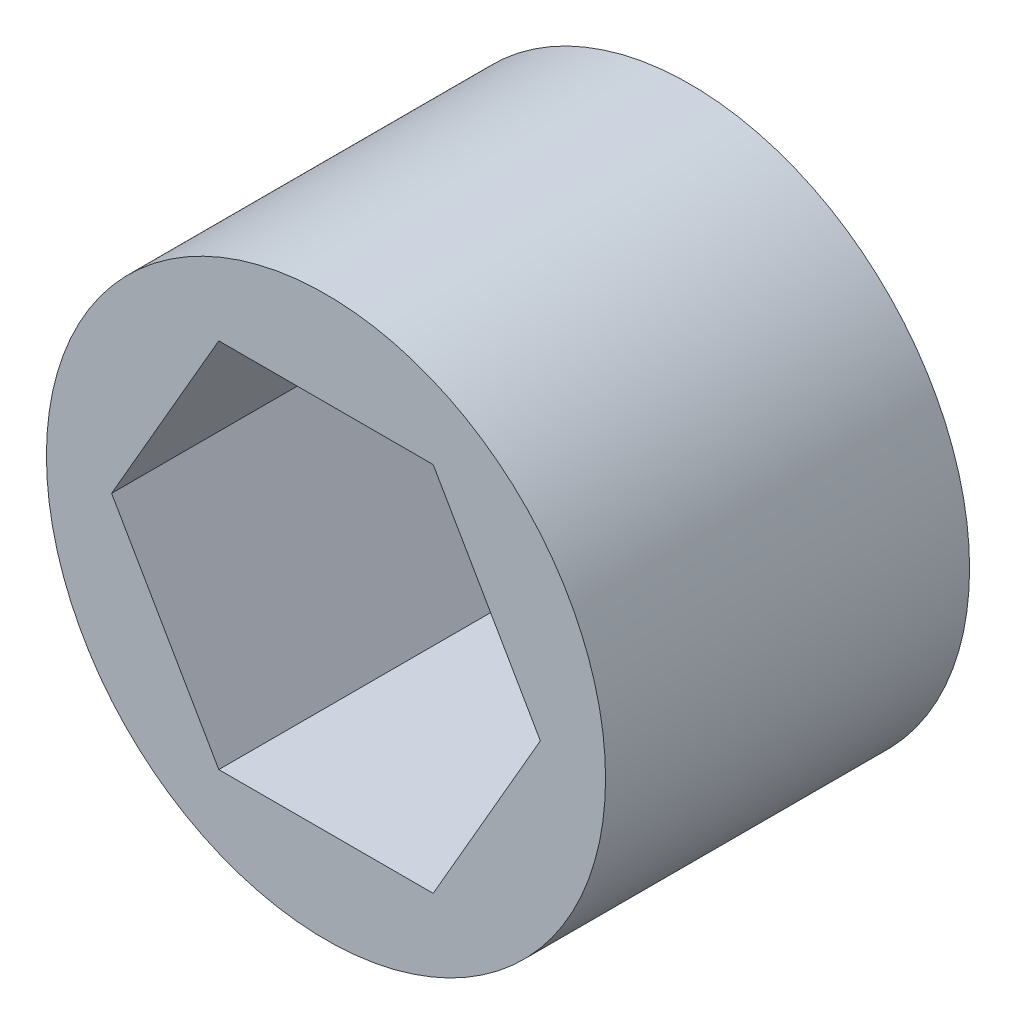
SolidWorks part; units mm, degrees
material "Delrin 2700 NC010, Low Viscosity Acetal Copolymer (SS)"
ref_plane "Front" through (0, 0, 0) normal (0, 0, 1) x (1, 0, 0)
ref_plane "Top" through (0, 0, 0) normal (0, 1, 0) x (1, 0, 0)
ref_plane "Right" through (0, 0, 0) normal (1, 0, 0) x (0, 0, -1)
sketch "Sketch2" plane through (0, 0, 0) normal (0, 0, 1) x (1, 0, 0)
  line L1 (-3.7395, 6.477) -> (-7.479, 0)
  line L2 (-7.479, 0) -> (-3.7395, -6.477)
  line L3 (-3.7395, -6.477) -> (3.7395, -6.477)
  line L4 (3.7395, -6.477) -> (7.479, 0)
  line L5 (7.479, 0) -> (3.7395, 6.477)
  line L6 (3.7395, 6.477) -> (-3.7395, 6.477)
  circle A0 centre (0, 0) radius 9.7536
  circle A1 centre (0, 0) radius 6.477 construction
  dimension "D1" = 19.5072
  dimension "D2" = 12.954
extrude "Boss-Extrude2" add sketch "Sketch2" along normal mid plane 12.7
